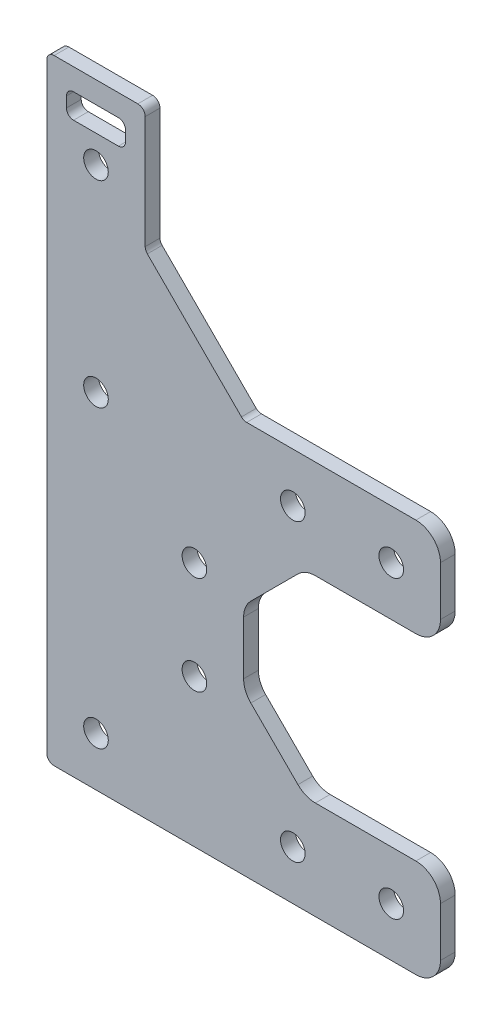
SolidWorks part; units mm, degrees
ref_plane "Front" through (0, 0, 0) normal (0, 0, 1) x (1, 0, 0)
ref_plane "Top" through (0, 0, 0) normal (0, 1, 0) x (1, 0, 0)
ref_plane "Right" through (0, 0, 0) normal (1, 0, 0) x (0, 0, -1)
sketch "Model" plane through (0, 0, 0) normal (0, 0, 1) x (1, 0, 0)
  line L0 (-36.75, 0) -> (36.75, 0)
  line L1 (-38.25, 123.5) -> (-38.25, 1.5)
  line L2 (36.75, 20) -> (16.3211, 20)
  line L3 (-34.25, 119.15) -> (-34.25, 117.03)
  line L4 (-22.25, 117.03) -> (-22.25, 119.15)
  line L5 (-18.25, 123.5) -> (-18.25, 100.6213)
  line L6 (3.2145, 31.0355) -> (12.7855, 21.4645)
  line L7 (1.75, 45.4289) -> (1.75, 34.5711)
  line L8 (36.75, 60) -> (16.3211, 60)
  line L9 (12.7855, 58.5355) -> (3.2145, 48.9645)
  line L10 (-17.8107, 99.5607) -> (1.3107, 80.4393)
  line L11 (36.75, 80) -> (2.3713, 80)
  line L12 (41.75, 5) -> (41.75, 15)
  line L13 (41.75, 65) -> (41.75, 75)
  line L14 (-32.81, 115.59) -> (-23.69, 115.59)
  line L15 (-23.69, 120.59) -> (-32.81, 120.59)
  line L16 (-19.75, 125) -> (-36.75, 125)
  line L17 (-28.25, 125) -> (-28.25, 0) construction
  line L18 (41.75, 70) -> (-38.25, 70) construction
  line L19 (41.75, 10) -> (-38.25, 10) construction
  line L20 (1.75, 40) -> (-38.25, 40) construction
  arc A0 (12.7855, 21.4645) -> (16.3211, 20) centre (16.3211, 25) ccw
  arc A1 (1.75, 34.5711) -> (3.2145, 31.0355) centre (6.75, 34.5711) ccw
  arc A2 (3.2145, 48.9645) -> (1.75, 45.4289) centre (6.75, 45.4289) ccw
  arc A3 (16.3211, 60) -> (12.7855, 58.5355) centre (16.3211, 55) ccw
  arc A4 (36.75, 0) -> (41.75, 5) centre (36.75, 5) ccw
  arc A5 (41.75, 15) -> (36.75, 20) centre (36.75, 15) ccw
  arc A6 (41.75, 75) -> (36.75, 80) centre (36.75, 75) ccw
  arc A7 (36.75, 60) -> (41.75, 65) centre (36.75, 65) ccw
  circle A8 centre (-28.25, 70) radius 2.5
  circle A9 centre (-8.25, 30) radius 2.5
  circle A10 centre (-8.25, 50) radius 2.5
  circle A11 centre (11.75, 70) radius 2.5
  circle A12 centre (31.75, 70) radius 2.5
  circle A13 centre (31.75, 10) radius 2.5
  circle A14 centre (11.75, 10) radius 2.5
  circle A15 centre (-28.25, 10) radius 2.5
  circle A16 centre (-28.25, 110) radius 2.5
  arc A17 (-18.25, 100.6213) -> (-17.8107, 99.5607) centre (-16.75, 100.6213) ccw
  arc A18 (1.3107, 80.4393) -> (2.3713, 80) centre (2.3713, 81.5) ccw
  arc A19 (-18.25, 123.5) -> (-19.75, 125) centre (-19.75, 123.5) ccw
  arc A20 (-36.75, 125) -> (-38.25, 123.5) centre (-36.75, 123.5) ccw
  arc A21 (-38.25, 1.5) -> (-36.75, 0) centre (-36.75, 1.5) ccw
  arc A22 (-32.81, 120.59) -> (-34.25, 119.15) centre (-32.81, 119.15) ccw
  arc A23 (-22.25, 119.15) -> (-23.69, 120.59) centre (-23.69, 119.15) ccw
  arc A24 (-23.69, 115.59) -> (-22.25, 117.03) centre (-23.69, 117.03) ccw
  arc A25 (-34.25, 117.03) -> (-32.81, 115.59) centre (-32.81, 117.03) ccw
  point P74 (-28.25, 115.59)
  dimension "D1" = 5
  dimension "D2" = 1.5
  dimension "D3" = 125
  dimension "D6" = 5
  dimension "D7" = 20
  dimension "D15" = 1.44
  dimension "D24" = 40
  dimension "D4" = 20
  dimension "D5" = 80
  dimension "D8" = 20
  dimension "D9" = 40
  dimension "D10" = 135
  dimension "D11" = 27.0416
  dimension "D12" = 15
  dimension "D13" = 10
  dimension "D14" = 30
  dimension "D16" = 5
  dimension "D17" = 12
  dimension "D18" = 4.41
  dimension "D19" = 30
  dimension "D20" = 20
  dimension "D21" = 10.8579
  dimension "D22" = 13.5355
  dimension "D23" = 135
  dimension "D25" = 10
extrude "Boss-Extrude1" add sketch "Model" along normal blind 3
